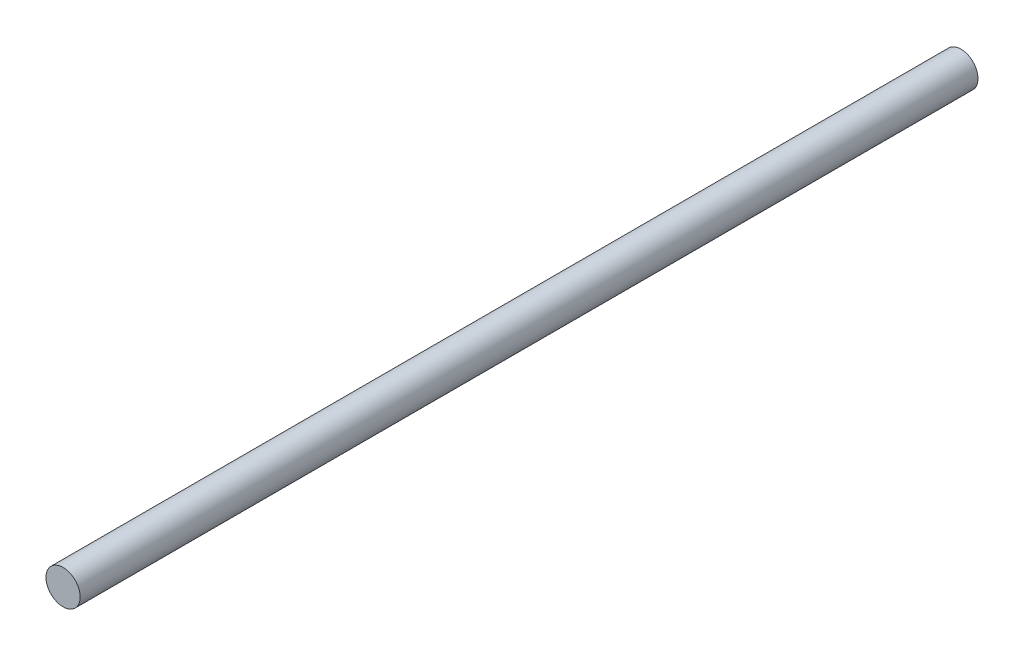
SolidWorks part; units mm, degrees
material "1060 Alloy"
ref_plane "Front Plane" through (0, 0, 0) normal (0, 0, 1) x (1, 0, 0)
ref_plane "Top Plane" through (0, 0, 0) normal (0, 1, 0) x (1, 0, 0)
ref_plane "Right Plane" through (0, 0, 0) normal (1, 0, 0) x (0, 0, -1)
sketch "Sketch1" plane through (0, 0, 0) normal (0, 0, 1) x (1, 0, 0)
  circle A0 centre (0, 0) radius 4
  dimension "D1" = 8
extrude "body" add sketch "Sketch1" along normal blind 210
